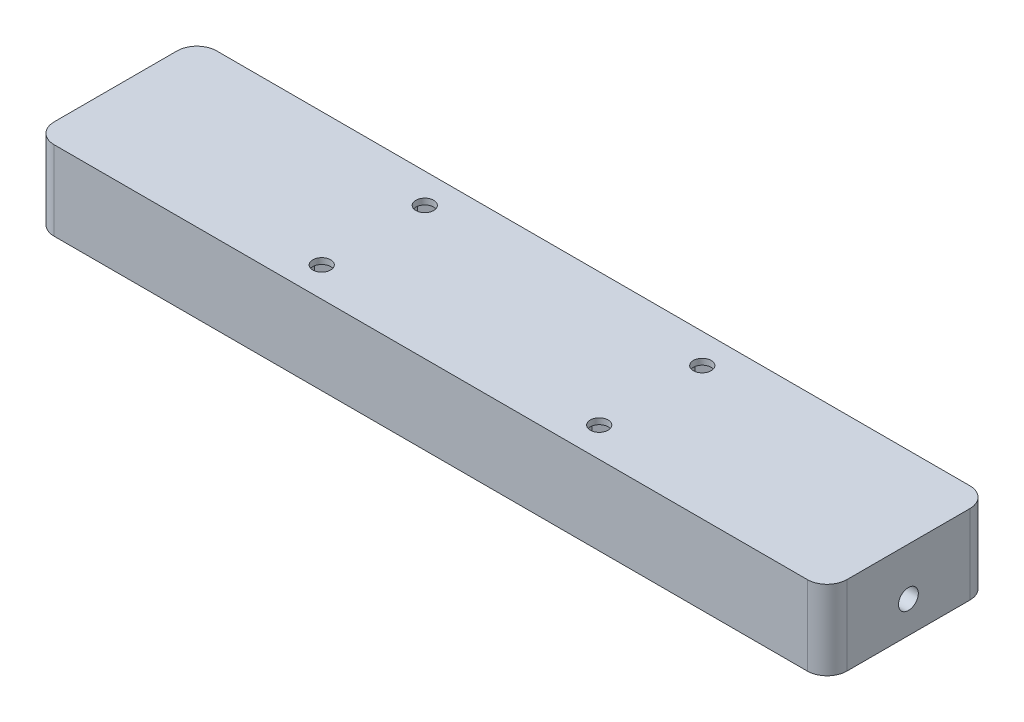
SolidWorks part; units mm, degrees
material "ABS"
ref_plane "Front Plane" through (0, 0, 0) normal (0, 0, 1) x (1, 0, 0)
ref_plane "Top Plane" through (0, 0, 0) normal (0, 1, 0) x (1, 0, 0)
ref_plane "Right Plane" through (0, 0, 0) normal (1, 0, 0) x (0, 0, -1)
sketch "Sketch1" plane through (0, 0, 0) normal (0, 1, 0) x (1, 0, 0)
  line L1 (0, 0) -> (200, 0)
  line L2 (0, 0) -> (0, 41)
  line L3 (0, 41) -> (200, 41)
  line L4 (200, 0) -> (200, 41)
  dimension "D1" = 41
  dimension "D2" = 200
extrude "Boss-Extrude1" add sketch "Sketch1" along normal blind 20
fillet "Fillet1" radius 5 4 edges at (200, 10, -41) (200, 10, 0) (0, 10, -41) (0, 10, 0)
sketch "Sketch4" plane through (0, 0, 0) normal (-1, 0, 0) x (0, 0, 1)
  line L4 (-36, 20) -> (-5, 20) construction
  line L5 (-36, 0) -> (-5, 0) construction
  circle A0 centre (-20.5, 8) radius 2.5
  point P5 (-20.5, 20)
  dimension "D1" = 8
  dimension "D2" = 5
extrude "Cut-Extrude1" cut sketch "Sketch4" against normal through all
sketch "Sketch5" plane through (0, 0, 0) normal (0, -1, 0) x (1, 0, 0)
  line L0 (195, -36) -> (5, -36)
  line L1 (5, -36) -> (5, -5)
  line L2 (5, -5) -> (195, -5)
  line L3 (0, -36) -> (0, -5) construction
  line L30 (195, -36) -> (195, -5)
  line L31 (5, -36) -> (195, -36)
  line L32 (5, -5) -> (5, -36)
  line L33 (195, -5) -> (5, -5)
  line L34 (195, -36) -> (195, -5)
  dimension "D2" = 5
  dimension "D1" = 5
extrude "Cut-Extrude2" cut sketch "Sketch5" against normal blind 15
hole_wizard "M4 Clearance Hole1" positions "3DSketch1" profile "Sketch6" hole size "M4" standard "ANSI Metric"
sketch3d "3DSketch1"
  line L2 (5, 20, 0) -> (195, 20, 0) construction
  line L3 (100, 20, -41) -> (100, 20, 0) construction
  line L4 (195, 20, -41) -> (5, 20, -41) construction
  line L5 (200, 20, -20.5) -> (0, 20, -20.5) construction
  line L6 (200, 20, -5) -> (200, 20, -36) construction
  line L7 (0, 20, -36) -> (0, 20, -5) construction
  point P0 (135, 20, -7.5)
  point P2 (65, 20, -33.5)
  point P13 (135, 20, -33.5)
  point P15 (65, 20, -7.5)
  dimension "D1" = 35
  dimension "D2" = 26
  dimension "D6" = 26
  dimension "D3" = 35
  dimension "D4" = 35
  dimension "D5" = 35
  dimension "D7" = 13
sketch "Sketch6" plane through (135, 20, -7.5) normal (1, 0, 0) x (0, 0, 1)
  line L0 (0, 0) -> (0, 9.3519)
  line L1 (0, 9.3519) -> (2.25, 8)
  line L2 (2.25, 8) -> (2.25, 0)
  line L5 (2.25, 0) -> (0, 0)
  line L10 (0, 9.3519) -> (-2.25, 8) construction
  line L11 (0, -6.35) -> (0, 107.95) construction
  dimension "Hole Dia." = 4.5
  dimension "Hole Depth" = 8
  dimension "Drill Angle" = 118
sketch "Sketch7" plane through (0, 15, 0) normal (0, -1, 0) x (1, 0, 0)
  line L1 (65, -12.4075) -> (69.25, -9.9537)
  line L2 (69.25, -9.9537) -> (69.25, -5.0463)
  line L3 (69.25, -5.0463) -> (65, -2.5925)
  line L4 (65, -2.5925) -> (60.75, -5.0463)
  line L5 (60.75, -5.0463) -> (60.75, -9.9537)
  line L6 (60.75, -9.9537) -> (65, -12.4075)
  circle A0 centre (65, -7.5) radius 4.25 construction
  dimension "D1" = 8.5
extrude "Cut-Extrude3" cut sketch "Sketch7" against normal blind 3.5 and the other way blind 4
pattern_linear "LPattern1" count 2 spacing 70 along (1, 0, 0) count 2 spacing 26 along (0, 0, -1) of "Cut-Extrude3"
